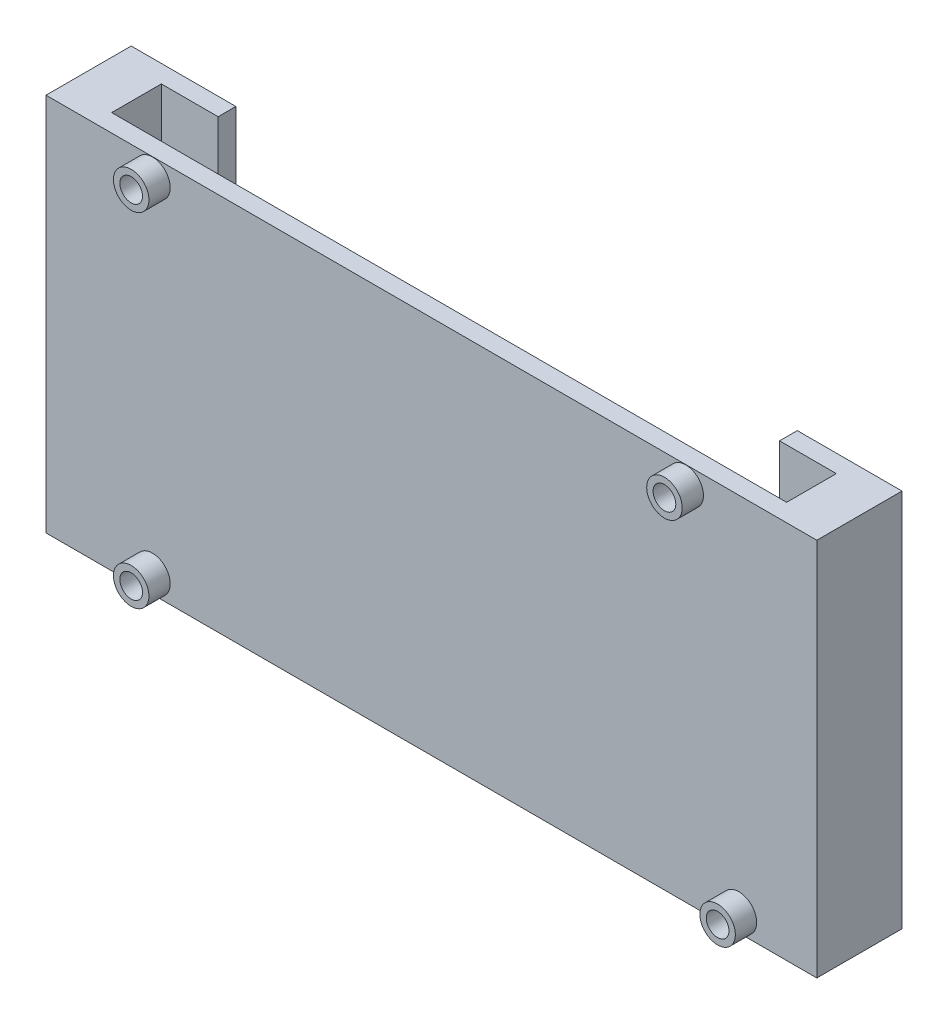
SolidWorks part; units mm, degrees
other "Markup1"
sketch "Sketch9" plane through (54.3, 26.7081, 7.5) normal (0.193, 0.975, 0.1103) x (0.9519, -0.1588, -0.262)
material "eSUN Tough Resin"
ref_plane "Front Plane" through (0, 0, 0) normal (0, 0, 1) x (1, 0, 0)
ref_plane "Top Plane" through (0, 0, 0) normal (0, 1, 0) x (1, 0, 0)
ref_plane "Right Plane" through (0, 0, 0) normal (1, 0, 0) x (0, 0, -1)
sketch "Sketch1" plane through (0, 0, 0) normal (0, 0, 1) x (1, 0, 0)
  line L1 (-54.3, -26.7081) -> (54.3, -26.7081)
  line L2 (-54.3, -26.7081) -> (-54.3, 26.7081)
  line L3 (-54.3, 26.7081) -> (54.3, 26.7081)
  line L4 (54.3, -26.7081) -> (54.3, 26.7081)
  line L5 (-54.3, -26.7081) -> (54.3, 26.7081) construction
  line L6 (-54.3, 26.7081) -> (54.3, -26.7081) construction
  point P0 (0, 0)
  dimension "D1" = 108.6
  dimension "D2" = 53.4162
extrude "Boss-Extrude1" add sketch "Sketch1" along normal blind 2.5
sketch "Sketch2" plane through (0, 0, 2.5) normal (0, 0, 1) x (1, 0, 0)
  line L0 (-54.3, 26.7081) -> (-54.3, -26.7081) construction
  line L1 (54.3, 26.7081) -> (-54.3, 26.7081) construction
  line L2 (-54.3, -26.7081) -> (54.3, -26.7081) construction
  circle A0 centre (-39.3, 24.1681) radius 2.5
  circle A1 centre (35.83, 24.1681) radius 2.5
  circle A2 centre (43.32, -24.1681) radius 2.5
  circle A3 centre (-39.3, -24.1681) radius 2.5
  dimension "D3" = 5
  dimension "D4" = 75.13
  dimension "D5" = 48.3362
  dimension "D6" = 15
  dimension "D2" = 2.54
  dimension "D7" = 82.62
  dimension "D8" = 2.54
extrude "Boss-Extrude2" add sketch "Sketch2" along normal blind 3
hole_wizard "M3 Clearance Hole1" positions "Sketch3" profile "Sketch4" hole size "M3" standard "ANSI Metric" end condition through all
sketch "Sketch3" plane through (0, 0, 5.5) normal (0, 0, 1) x (1, 0, 0)
  circle A0 centre (35.83, 24.1681) radius 2.5 construction
  point P0 (-39.3, 24.1681)
  point P3 (35.83, 24.1681)
  point P5 (43.32, -24.1681)
  point P8 (-39.3, -24.1681)
sketch "Sketch4" plane through (-39.3, 24.1681, 5.5) normal (1, 0, 0) x (0, -1, 0)
  line L0 (0, 0) -> (0, 5.5)
  line L1 (0, 5.5) -> (1.6, 5.5)
  line L2 (1.6, 5.5) -> (1.6, 0)
  line L5 (1.6, 0) -> (0, 0)
  line L11 (0, -6.35) -> (0, 107.95) construction
  dimension "Thru Hole Dia." = 3.2
  dimension "Thru Hole Depth" = 5.5
sketch "Sketch5" plane through (0, 0, 0) normal (0, 0, -1) x (-1, 0, 0)
  line L0 (54.3, -26.7081) -> (-54.3, -26.7081) construction
  line L1 (-54.3, 26.7081) -> (-47.55, 26.7081)
  line L2 (-54.3, 26.7081) -> (-54.3, -26.7081)
  line L3 (-54.3, -26.7081) -> (-47.55, -26.7081)
  line L4 (-47.55, 26.7081) -> (-47.55, -26.7081)
  line L6 (54.3, 26.7081) -> (47.55, 26.7081)
  line L7 (54.3, 26.7081) -> (54.3, -26.7081)
  line L8 (54.3, -26.7081) -> (47.55, -26.7081)
  line L9 (47.55, 26.7081) -> (47.55, -26.7081)
  dimension "D1" = 6.75
  dimension "D2" = 6.75
extrude "Boss-Extrude3" add sketch "Sketch5" along normal blind 9.5
sketch "Sketch6" plane through (47.55, 0, 0) normal (-1, 0, 0) x (0, 0, 1)
  line L0 (2.5, -26.7081) -> (-9.5, -26.7081) construction
  line L1 (-9.5, 26.7081) -> (-7, 26.7081)
  line L2 (-9.5, 26.7081) -> (-9.5, -26.7081)
  line L3 (-9.5, -26.7081) -> (-7, -26.7081)
  line L4 (-7, 26.7081) -> (-7, -26.7081)
  dimension "D1" = 2.5
extrude "Boss-Extrude4" add sketch "Sketch6" along normal blind 8
sketch "Sketch7" plane through (-47.55, 0, 0) normal (1, 0, 0) x (0, 0, -1)
  line L0 (-2.5, -26.7081) -> (9.5, -26.7081) construction
  line L1 (9.5, 26.7081) -> (7, 26.7081)
  line L2 (9.5, 26.7081) -> (9.5, -26.7081)
  line L3 (9.5, -26.7081) -> (7, -26.7081)
  line L4 (7, 26.7081) -> (7, -26.7081)
  dimension "D1" = 2.5
extrude "Boss-Extrude5" add sketch "Sketch7" along normal blind 8
sketch "Sketch8" plane through (0, -26.7081, 0) normal (0, -1, 0) x (1, 0, 0)
  line L0 (-54.3, -3.5) -> (54.3, -3.5) construction
  line L1 (-54.3, 2.5) -> (-54.3, -9.5) construction
  line L2 (54.3, 2.5) -> (54.3, -9.5) construction
  line L3 (-47.55, 0) -> (-54.3, 0) construction
  line L4 (-50.925, 0) -> (-50.925, -9.5) construction
  line L5 (-39.55, -9.5) -> (-54.3, -9.5) construction
  line L6 (47.55, 0) -> (54.3, 0) construction
  line L7 (50.925, 0) -> (50.925, -9.5) construction
  line L8 (54.3, -9.5) -> (39.55, -9.5) construction
  circle A0 centre (-50.925, -3.5) radius 3.15
  circle A1 centre (50.925, -3.5) radius 3.15
  dimension "D1" = 6.3
extrude "Cut-Extrude1" cut sketch "Sketch8" against normal blind 2.7
